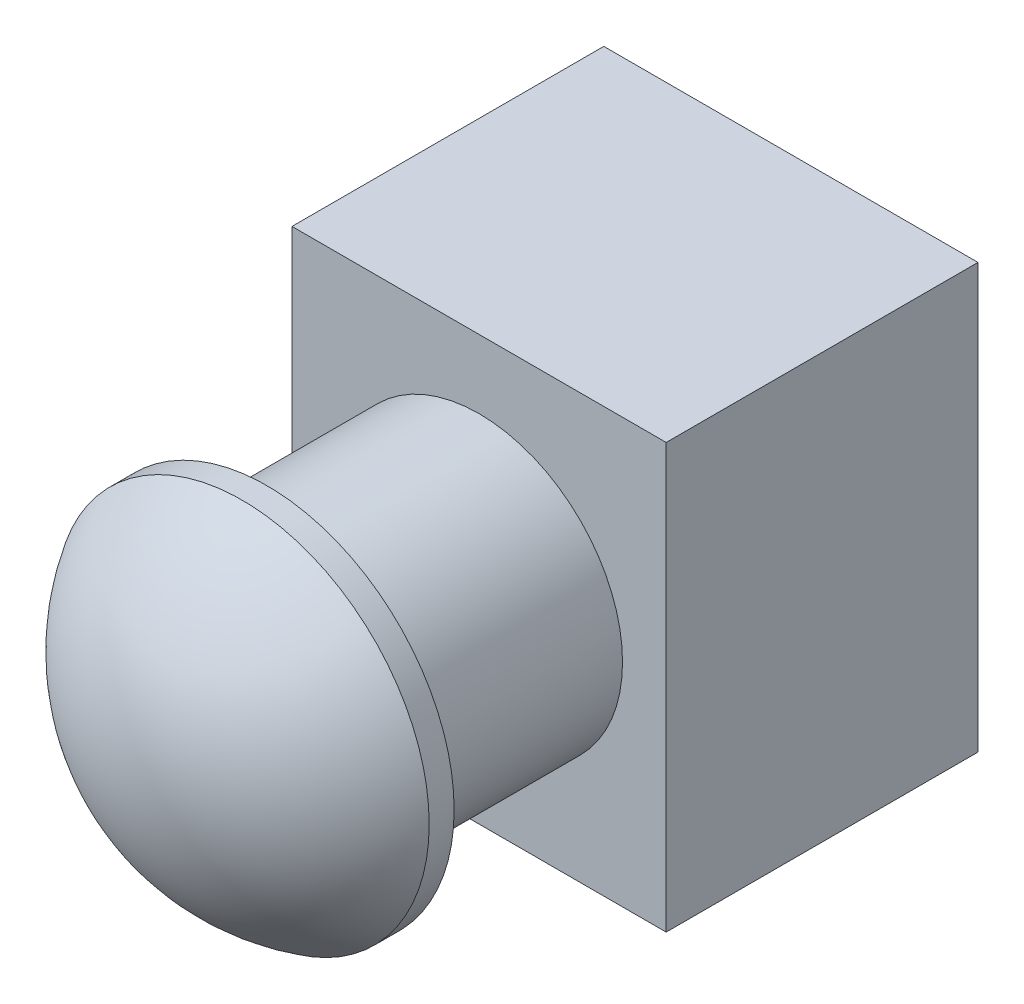
SolidWorks part; units mm, degrees
ref_plane "前视基准面" through (0, 0, 0) normal (0, 0, 1) x (1, 0, 0)
ref_plane "上视基准面" through (0, 0, 0) normal (0, 1, 0) x (1, 0, 0)
ref_plane "右视基准面" through (0, 0, 0) normal (1, 0, 0) x (0, 0, -1)
sketch "草图1" plane through (0, 0, 0) normal (0, 0, 1) x (1, 0, 0)
  line L1 (-15, -17) -> (15, -17)
  line L2 (-15, -17) -> (-15, 17)
  line L3 (-15, 17) -> (15, 17)
  line L4 (15, -17) -> (15, 17)
  line L5 (-15, -17) -> (15, 17) construction
  line L6 (-15, 17) -> (15, -17) construction
  point P0 (0, 0)
  dimension "D1" = 34
  dimension "D2" = 30
extrude "凸台-拉伸1" add sketch "草图1" along normal blind 25
sketch "草图2" plane through (0, 0, 25) normal (0, 0, 1) x (1, 0, 0)
  circle A0 centre (0, 0) radius 11.5
  dimension "D1" = 23
extrude "凸台-拉伸2" add sketch "草图2" along normal blind 17
sketch "草图3" plane through (0, 0, 0) normal (0, 1, 0) x (1, 0, 0)
  line L0 (0, -42) -> (15, -42)
  line L1 (-11.5, -42) -> (11.5, -42) construction
  line L2 (15, -42) -> (15, -44)
  line L3 (0, -42) -> (0, -52) construction
  line L4 (0, -52) -> (0, -35) construction
  line L5 (0, -42) -> (0, -52.4929)
  arc A0 (0, -52.4929) -> (15, -44) centre (0, -35) ccw
  dimension "D1" = 15
  dimension "D2" = 2
  dimension "D3" = 10
  dimension "D4" = 17
revolve "旋转1" add sketch "草图3" angle 360 about L5
